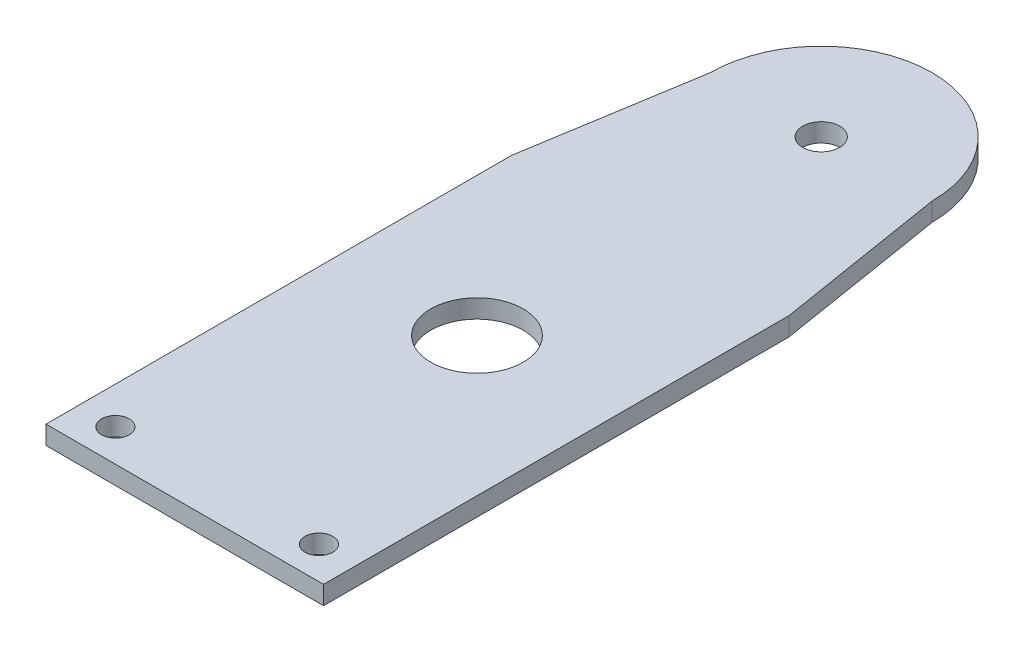
SolidWorks part; units mm, degrees
ref_plane "Спереди" through (0, 0, 0) normal (0, 0, 1) x (1, 0, 0)
ref_plane "Сверху" through (0, 0, 0) normal (0, 1, 0) x (1, 0, 0)
ref_plane "Справа" through (0, 0, 0) normal (1, 0, 0) x (0, 0, -1)
sketch "Эскиз1" plane through (0, 0, 0) normal (0, 1, 0) x (1, 0, 0)
  line L0 (-17.6252, -26.1173) -> (12.3748, -26.1173) construction
  line L1 (-17.6252, -29.6173) -> (12.3748, -29.6173) construction
  line L2 (-17.6252, -29.6173) -> (-17.6252, 48.1827) construction
  line L3 (-17.6252, 52.3827) -> (12.3748, 52.3827) construction
  line L4 (5.3748, -19.6173) -> (5.3748, -29.6173) construction
  line L5 (-13.6252, -27.6173) -> (8.3748, -27.6173) construction
  line L6 (-2.6252, -29.6173) -> (-2.6252, 60.301) construction
  line L7 (12.3748, -29.6173) -> (12.3748, 20.6827)
  line L8 (12.3748, 20.6827) -> (9.3748, 39.1827)
  line L9 (5.3748, -19.6173) -> (-10.6252, -19.6173) construction
  line L10 (5.3748, -29.6173) -> (12.3748, -29.6173)
  line L11 (-10.6252, -19.6173) -> (-10.6252, -29.6173) construction
  line L12 (-10.6252, -29.6173) -> (-17.6252, -29.6173)
  line L13 (-10.6252, -29.6173) -> (5.3748, -29.6173)
  line L14 (-17.6252, -29.6173) -> (-17.6252, 20.6827)
  line L15 (-17.6252, 20.6827) -> (-14.6252, 39.1827)
  circle A0 centre (-13.6252, -26.1173) radius 1.5
  circle A1 centre (8.3748, -26.1173) radius 1.5
  circle A2 centre (-2.6252, 39.1827) radius 2
  arc A3 (9.3748, 39.1827) -> (-14.6252, 39.1827) centre (-2.6252, 39.1827) ccw
  circle A4 centre (-2.6252, 1.9727) radius 5
  point P23 (-2.6252, -19.6173)
  dimension "D3" = 68.8
  dimension "D4" = 4
  dimension "D7" = 3
  dimension "D8" = 7
  dimension "D1" = 3.5
  dimension "D10" = 37.21
  dimension "D11" = 10
  dimension "D12" = 12
  dimension "D2" = 30
  dimension "D5" = 22
  dimension "D6" = 4
  dimension "D9" = 10
  dimension "D13" = 50.3
extrude "Бобышка-Вытянуть1" add sketch "Эскиз1" along normal blind 2
